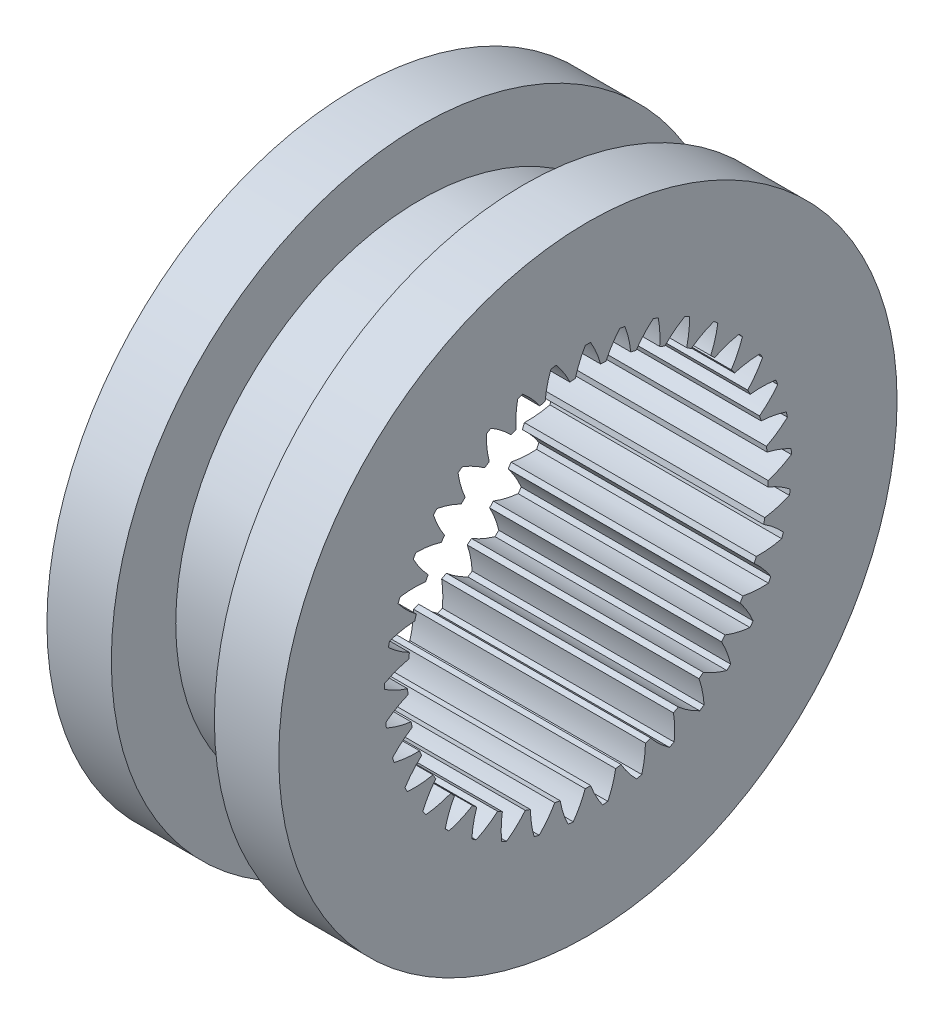
SolidWorks part; units mm, degrees
ref_plane "Plane1" through (0, 0, 0) normal (0, 0, 1) x (1, 0, 0)
ref_plane "Plane2" through (0, 0, 0) normal (0, 1, 0) x (1, 0, 0)
ref_plane "Plane3" through (0, 0, 0) normal (1, 0, 0) x (0, 0, -1)
other "Configuration Table"
sketch "HoldingSke" plane through (0, 0, 0) normal (0, 1, 0) x (1, 0, 0)
  line L0 (0, 0) -> (0.9983, -0.7523)
  line L1 (-15, 0) -> (100, 0) construction
  line L2 (0, 0) -> (-2.1039, 2.3779)
  line L3 (0, 0) -> (-11.863, 4.5341)
  line L4 (0, 0) -> (6.897, 5.1973)
  line L5 (0, 0) -> (-23.7986, -8.8762)
  line L6 (0, 0) -> (-10.5278, -7.1032)
  line L7 (-2.1039, 2.3779) -> (3.3635, 27.1825)
  line L8 (-76.2, 3.1779) -> (-54.61, 3.1779)
  line L9 (-71.009, 38.7566) -> (-53.1078, 45.2721)
  line L10 (-76.2, 71.12) -> (104.1128, 71.12)
  line L11 (0, 0) -> (-18, 0)
  line L12 (-76.2, 101.6) -> (-76.17, 101.6)
  line L13 (24.9733, 27.94) -> (52.9518, 28.4284)
  line L14 (24.9733, 27.94) -> (24.9743, 27.94)
  line L15 (24.9733, 27.94) -> (100.4006, 29.5858)
  circle A0 centre (0, 0) radius 21.5
  circle A1 centre (0, 0) radius 12.7
  circle A2 centre (0, 0) radius 12.7
  dimension "MHD" = 25.4
  dimension "Hub_dia" = 25.4
  dimension "Diameter" = 43
  dimension "Num_teeth" = 37
  dimension "Pitch" = 1.25
  dimension "Overall_len" = 25.4
  dimension "Show_teeth" = 37
  dimension "Thickness" = 12.7
  dimension "OAL" = 25.4001
  dimension "T_dim" = 21.59
  dimension "Ap" = 20
  dimension "H" = 19.05
  dimension "Pitch_radius" = 180.3128
  dimension "Width" = 18
  dimension "Backlash" = 0.03
  dimension "Addendum_fac" = 1
  dimension "Dedendum_fac" = 1.25
  dimension "Clearance_fac" = 0.25
  dimension "Dedendum_add" = 0.001
  dimension "Module" = 0.8
sketch "BasProSke" plane through (0, 0, 0) normal (0, 1, 0) x (1, 0, 0)
  line L0 (-10, 0) -> (60, 0) construction
  line L1 (0, 14) -> (0, 24)
  line L2 (0, 14) -> (18, 14)
  line L3 (18, 14) -> (18, 24)
  line L5 (0, 24) -> (5, 24)
  line L6 (5, 24) -> (5, 19)
  line L7 (5, 19) -> (13, 19)
  line L8 (13, 19) -> (13, 24)
  line L9 (13, 24) -> (18, 24)
  dimension "Thickness" = 18
  dimension "Inside_diameter" = 28
revolve "Base-Revolve" add sketch "BasProSke" angle 360 about L0
sketch "TooCutSke" plane through (0, 0, 0) normal (1, 0, 0) x (0, 0, -1)
  line L3 (0.7031, 14.7833) -> (0.7031, 53.6633) construction
  line L4 (0, 0) -> (0, 59.563) construction
  line L5 (0, 0) -> (-5.7946, 68.0813) construction
  line L6 (-6.1684, 12.037) -> (36.645, 15.6809) construction
  circle A0 centre (0, 0) radius 14.8 construction
  circle A1 centre (0, 0) radius 15.801 construction
  circle A2 centre (0, 0) radius 12.5167 construction
  circle A3 centre (0, 0) radius 13.9746 construction
  arc A4 (0.9827, 13.94) -> (0.2036, 15.7997) centre (-6.1684, 12.037) ccw
  arc A5 (0.9827, 13.94) -> (-0.9827, 13.94) centre (0, 0) ccw
  arc A6 (0.2036, 15.7997) -> (-0.2036, 15.7997) centre (0, 0) ccw
  arc A7 (-0.2036, 15.7997) -> (-0.9827, 13.94) centre (6.1684, 12.037) ccw
  dimension "Pitch_dia" = 29.6
  dimension "Base_dia" = 25.0334
  dimension "Root_dia" = 31.602
  dimension "Overcut_dia" = 27.9492
  dimension "Flank_rad" = 7.4
  dimension "Half_ang" = 4.865
  dimension "Half_CT" = 0.7031
extrude "ToothCut" cut sketch "TooCutSke" along normal through all
fillet "Breaks" [suppressed] radius 0.08
fillet "RootFillets" [suppressed] radius 0.201
pattern_circular "TeethCuts" count 37 every 9.73 about axis through (-10, 0, 0) along (1, 0, 0) of "RootFillets", "Breaks", "ToothCut"
equation "' \"Module@HoldingSke\" = 6.35"
equation "' \"Num_teeth@HoldingSke\" = 24"
equation "' \"Ap@HoldingSke\" =  14.5"
equation "' \"Ap@HoldingSke\" = 14.5"
equation "' \"Width@HoldingSke\" = 12"
equation "' \"Diameter@HoldingSke\" = 8 * 25.4"
equation "' \"Show_teeth@HoldingSke\" = 100"
equation "' \"Backlash@HoldingSke\" = 0.009 * 25.4"
equation "' \"Addendum_fac@HoldingSke\" = 1.0"
equation "' \"Dedendum_fac@HoldingSke\" = 1.25"
equation "' \"Dedendum_add@HoldingSke\" = 0.00005 * 25.4"
equation "' \"Clearance_fac@HoldingSke\" = 0.25"
equation "\"Pitch@HoldingSke\" = 1 / \"Module@HoldingSke\" "
equation "\"Overcut_dia@TooCutSke\" = (\"Num_teeth@HoldingSke\" - 2 * \"Addendum_fac@HoldingSke\") / \"Pitch@HoldingSke\" - 0.002 * 25.4"
equation "\"Pitch_dia@TooCutSke\" = \"Num_teeth@HoldingSke\" / \"Pitch@HoldingSke\""
equation "\"Base_dia@TooCutSke\" = \"Num_teeth@HoldingSke\" / \"Pitch@HoldingSke\" * cos((\"Ap@HoldingSke\"  * 3.14159265 / 180)) * 0.90"
equation "\"Root_dia@TooCutSke\" = \"Num_teeth@HoldingSke\"  / \"Pitch@HoldingSke\" + 2 *  \"Dedendum_fac@HoldingSke\"/ \"Pitch@HoldingSke\" + \"Dedendum_add@HoldingSke\" * 2"
equation "\"Half_ang@TooCutSke\" = 180 / \"Num_teeth@HoldingSke\""
equation "\"Half_CT@TooCutSke\" = \"Num_teeth@HoldingSke\" / \"Pitch@HoldingSke\" * sin((3.14159265 / 2 / \"Num_teeth@HoldingSke\")) / 2 + 10 * \"Backlash@HoldingSke\" / 4"
equation "\"Flank_rad@TooCutSke\" = \"Num_teeth@HoldingSke\" / \"Pitch@HoldingSke\" / 4"
equation "\"Radius@RootFillets\"= \"Clearance_fac@HoldingSke\" / \"Pitch@HoldingSke\" + \"Dedendum_add@HoldingSke\""
equation "\"Break_rad@Breaks\" = 0.02 / \"Pitch@HoldingSke\" * 5"
equation "\"Num_teeth@TeethCuts\" = int( \"Show_teeth@HoldingSke\" ) + 1"
equation "\"Num_teeth@TeethCuts\" = ((sgn( \"Num_teeth@TeethCuts\" - \"Num_teeth@HoldingSke\" )-1)*( \"Num_teeth@TeethCuts\" - \"Num_teeth@HoldingSke\" ))/-2+ \"Num_teeth@HoldingSke\""
equation "\"Num_teeth@TeethCuts\" = ((sgn( \"Num_teeth@TeethCuts\" - 2.0)+1)*( \"Num_teeth@TeethCuts\" - 2.0))/2 +2.0"
equation "\"Angle@TeethCuts\" = 360.0 / \"Num_teeth@HoldingSke\""
equation "\"Diameter@BasProSke\" = ((sgn( \"Diameter@BasProSke\"  - \"Diameter@HoldingSke\" )+1)*( \"Diameter@BasProSke\"  - \"Diameter@HoldingSke\" ))/2 + \"Diameter@HoldingSke\""
equation "\"Inside_diameter@BasProSke\" =  (\"Num_teeth@HoldingSke\" - 2 * \"Addendum_fac@HoldingSke\") / \"Pitch@HoldingSke\" "
equation "\"Thickness@BasProSke\"  = \"Width@HoldingSke\""
